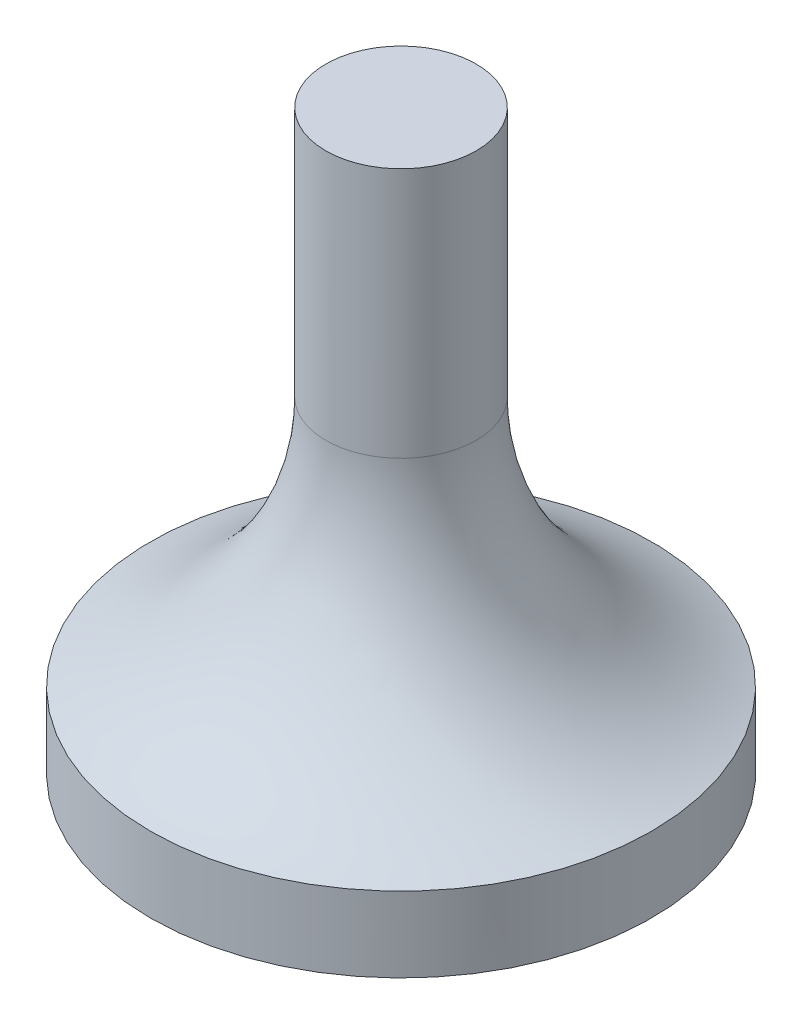
SolidWorks part; units mm, degrees
ref_plane "前视基准面" through (0, 0, 0) normal (0, 0, 1) x (1, 0, 0)
ref_plane "上视基准面" through (0, 0, 0) normal (0, 1, 0) x (1, 0, 0)
ref_plane "右视基准面" through (0, 0, 0) normal (1, 0, 0) x (0, 0, -1)
other "Configuration Table"
sketch "草图1" plane through (0, 0, 0) normal (0, 1, 0) x (1, 0, 0)
  circle A0 centre (0, 0) radius 10
  dimension "D1" = 20
extrude "凸台-拉伸1" add sketch "草图1" along normal blind 3
sketch "草图2" plane through (0, 3, 0) normal (0, 1, 0) x (1, 0, 0)
  circle A0 centre (0, 0) radius 3
  dimension "D1" = 6
extrude "凸台-拉伸2" add sketch "草图2" along normal blind 20
sketch "草图3" plane through (0, 0, 0) normal (0, 0, 1) x (1, 0, 0)
  line L1 (-3, 23) -> (-3, 3) construction
  line L2 (-10, 3) -> (-3, 3)
  line L3 (-3, 3) -> (-3, 13)
  line L4 (0, -1000) -> (0, 49000) construction
  arc A0 (-3, 13) -> (-10, 3) centre (-13.6429, 13) cw
revolve "旋转2" add sketch "草图3" angle 360 about L4
